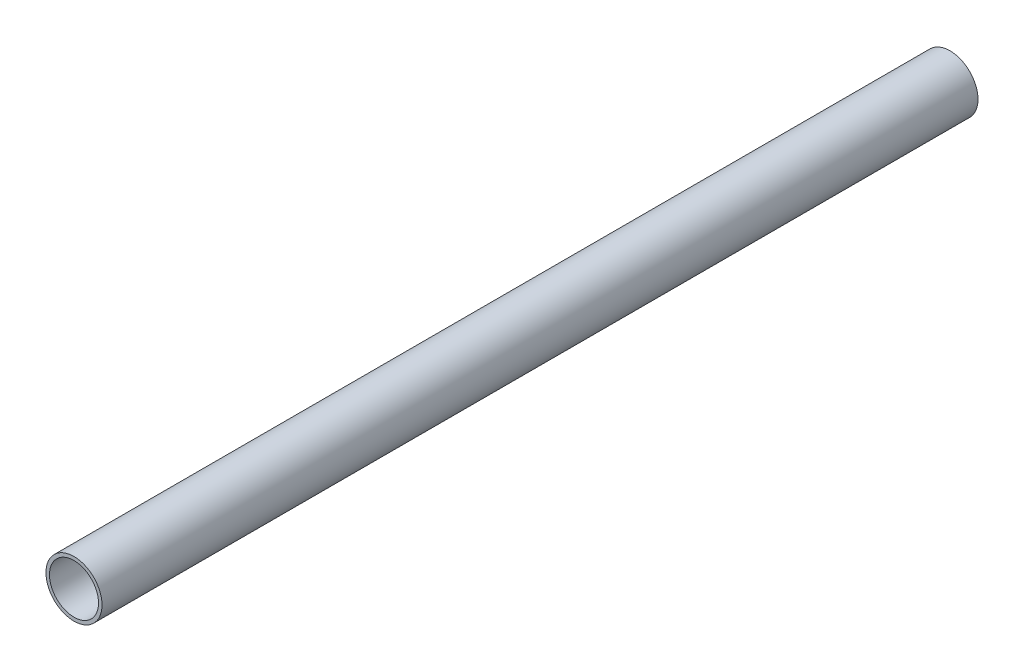
SolidWorks part; units mm, degrees
ref_plane "Front Plane" through (0, 0, 0) normal (0, 0, 1) x (1, 0, 0)
ref_plane "Top Plane" through (0, 0, 0) normal (0, 1, 0) x (1, 0, 0)
ref_plane "Right Plane" through (0, 0, 0) normal (1, 0, 0) x (0, 0, -1)
sketch "Sketch1" plane through (0, 0, 0) normal (0, 0, 1) x (1, 0, 0)
  circle A0 centre (0, 0) radius 7
  circle A1 centre (0, 0) radius 8
  dimension "D1" = 16
  dimension "D2" = 14
extrude "Boss-Extrude1" add sketch "Sketch1" along normal blind 250
